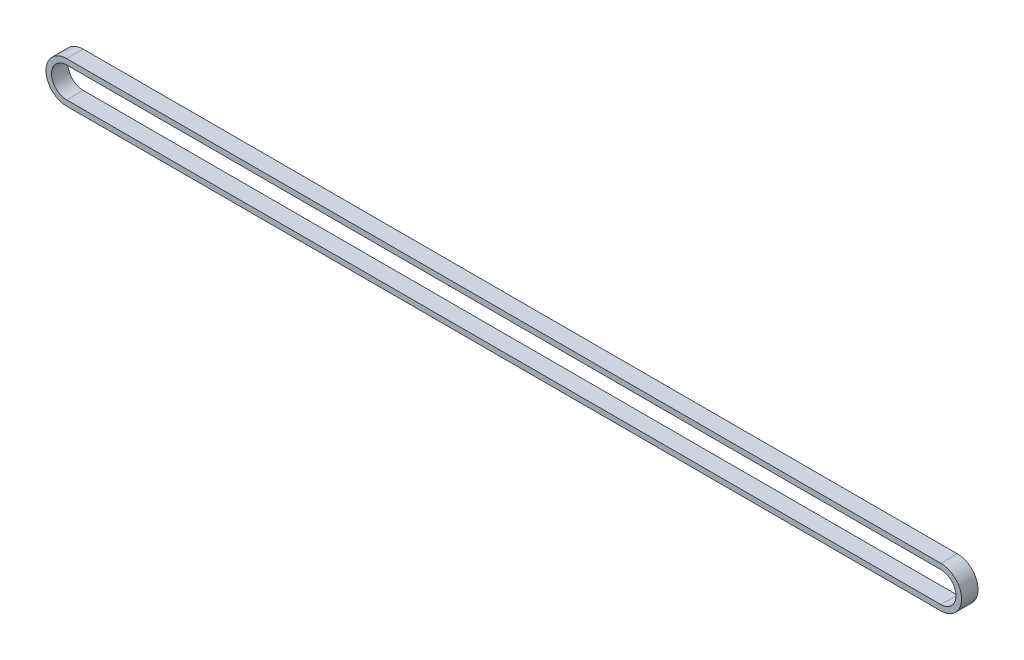
SolidWorks part; units mm, degrees
ref_plane "前视基准面" through (0, 0, 0) normal (0, 0, 1) x (1, 0, 0)
ref_plane "上视基准面" through (0, 0, 0) normal (0, 1, 0) x (1, 0, 0)
ref_plane "右视基准面" through (0, 0, 0) normal (1, 0, 0) x (0, 0, -1)
other "Configuration Table"
sketch "草图1" plane through (0, 0, 0) normal (0, 0, 1) x (1, 0, 0)
  line L0 (0, 0) -> (318, 0) construction
  line L1 (0, 5.5) -> (318, 5.5)
  line L2 (0, -5.5) -> (318, -5.5)
  line L3 (0, 0) -> (318, 0) construction
  line L4 (0, 7.5) -> (318, 7.5)
  line L5 (0, -7.5) -> (318, -7.5)
  arc A0 (0, 5.5) -> (0, -5.5) centre (0, 0) ccw
  arc A1 (318, -5.5) -> (318, 5.5) centre (318, 0) ccw
  arc A2 (0, 7.5) -> (0, -7.5) centre (0, 0) ccw
  arc A3 (318, -7.5) -> (318, 7.5) centre (318, 0) ccw
  point P3 (159, 0)
  point P10 (159, 0)
  dimension "D2" = 5.5
  dimension "D1" = 318
  dimension "D3" = 2
extrude "凸台-拉伸1" add sketch "草图1" along normal blind 6
